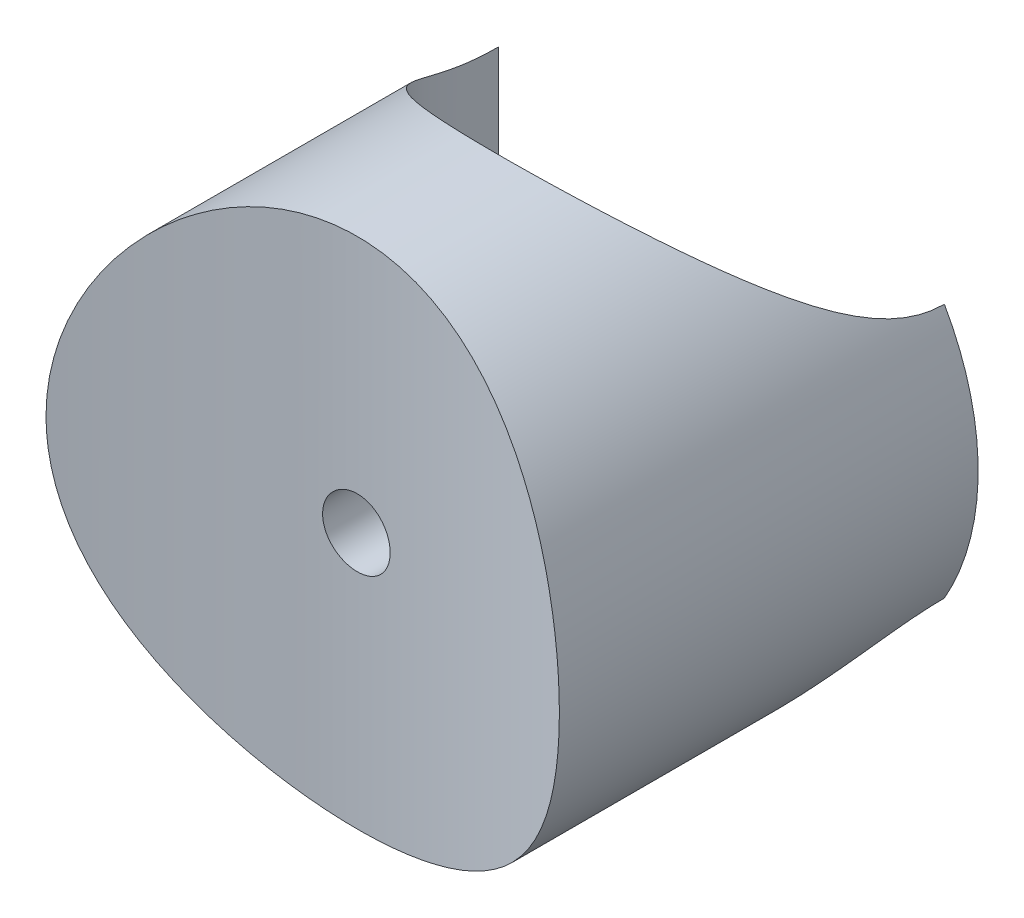
SolidWorks part; units mm, degrees
material "Alumina"
ref_plane "Plano frontal" through (0, 0, 0) normal (0, 0, 1) x (1, 0, 0)
ref_plane "Plano superior" through (0, 0, 0) normal (0, 1, 0) x (1, 0, 0)
ref_plane "Plano direito" through (0, 0, 0) normal (1, 0, 0) x (0, 0, -1)
sketch "Esboço1" plane through (0, 0, 0) normal (0, 0, 1) x (1, 0, 0)
  circle A0 centre (0, 0) radius 19
  dimension "D1" = 38
extrude "Ressalto-extrusão1" add sketch "Esboço1" along normal mid plane 15
sketch "Esboço2" plane through (0, 0, 0) normal (0, 1, 0) x (1, 0, 0)
  line L0 (-19, 7.5) -> (-19, -7.5) construction
  line L1 (19, -7.5) -> (19, 7.5) construction
  line L2 (19, 7.5) -> (-19, 7.5) construction
  arc A0 (-19, 1.5) -> (19, 1.5) centre (0, -41.1335) cw
  dimension "D1" = 6
  dimension "D3" = 5.5421
  dimension "D2" = 6
extrude "Corte-extrusão1" cut sketch "Esboço2" against normal through all and the other way through all flip side to cut
sketch "Esboço7" plane through (0, 0, -7.5) normal (0, 0, -1) x (-1, 0, 0)
  circle A0 centre (0, 0) radius 19
extrude "Ressalto-extrusão3" add sketch "Esboço7" along normal blind 25
sketch "Esboço8" plane through (0, 0, 0) normal (0, 1, 0) x (1, 0, 0)
  line L0 (19, 32.5) -> (-19, 32.5) construction
  circle A0 centre (0, 32.5) radius 16.5
  dimension "D1" = 33
extrude "Corte-extrusão2" cut sketch "Esboço8" against normal mid plane 58
hole_wizard "Furo roscado de M62" positions "Esboço9" profile "Esboço10" tap size "M6" standard "DIN" end condition through all
sketch "Esboço9" plane through (0, 0, 0) normal (0, 0, 1) x (1, 0, 0)
  point P0 (0, 0)
sketch "Esboço10" plane through (0, 0, 0) normal (1, 0, 0) x (0, -1, 0)
  line L0 (0, 0) -> (0, 33.7397)
  line L1 (0, 33.7397) -> (2.5, 33.7397)
  line L2 (2.5, 33.7397) -> (2.5, 0)
  line L5 (2.5, 0) -> (0, 0)
  line L11 (0, -6.35) -> (0, 107.95) construction
  dimension "Thru Tap Drill Dia." = 5
  dimension "Thru Tap Drill Depth" = 33.7397
cosmetic thread "Rosca de furo2" parameters "D2"=6
